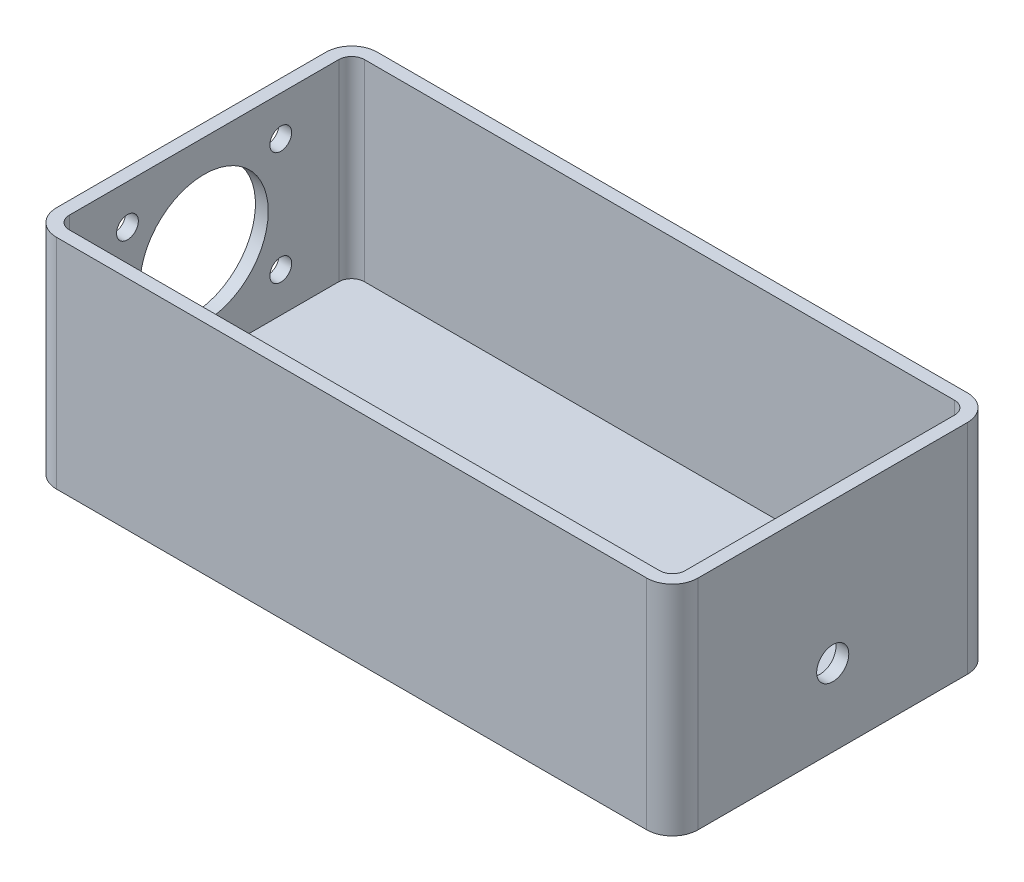
SolidWorks part; units mm, degrees
ref_plane "Front Plane" through (0, 0, 0) normal (0, 0, 1) x (1, 0, 0)
ref_plane "Top Plane" through (0, 0, 0) normal (0, 1, 0) x (1, 0, 0)
ref_plane "Right Plane" through (0, 0, 0) normal (1, 0, 0) x (0, 0, -1)
sketch "Sketch1" plane through (0, 0, 0) normal (0, 1, 0) x (1, 0, 0)
  line L1 (0, 0) -> (127, 0)
  line L2 (0, 0) -> (0, 63.5)
  line L3 (0, 63.5) -> (127, 63.5)
  line L4 (127, 0) -> (127, 63.5)
  dimension "D1" = 63.5
  dimension "D2" = 127
extrude "Boss-Extrude1" add sketch "Sketch1" along normal blind 5.08
sketch "Sketch2" plane through (0, 5.08, 0) normal (0, 1, 0) x (1, 0, 0)
  line L1 (0, 63.5) -> (127, 63.5)
  line L2 (0, 63.5) -> (0, 0)
  line L3 (0, 0) -> (127, 0)
  line L4 (127, 63.5) -> (127, 0)
  line L5 (2.54, 60.96) -> (124.46, 60.96)
  line L6 (2.54, 60.96) -> (2.54, 2.54)
  line L7 (2.54, 2.54) -> (124.46, 2.54)
  line L8 (124.46, 60.96) -> (124.46, 2.54)
  dimension "D1" = 2.54
  dimension "D2" = 2.54
  dimension "D3" = 2.54
  dimension "D4" = 2.54
extrude "Boss-Extrude3" add sketch "Sketch2" along normal blind 38.1
sketch "Sketch3" plane through (0, 0, 0) normal (-1, 0, 0) x (0, 0, 1)
  circle A0 centre (-31.75, 24.13) radius 12.7
  circle A1 centre (-46.9265, 35.3568) radius 2.159
  circle A2 centre (-16.5735, 35.3568) radius 2.159
  circle A3 centre (-46.9265, 12.9032) radius 2.159
  circle A4 centre (-16.5735, 12.9032) radius 2.159
  point P10 (0, 0)
  dimension "D1" = 25.4
  dimension "D2" = 4.318
  dimension "D3" = 4.318
  dimension "D4" = 4.318
  dimension "D5" = 4.318
  dimension "D6" = 30.353
  dimension "D7" = 22.4536
  dimension "D8" = 15.1765
  dimension "D9" = 11.2268
  dimension "D10" = 24.13
  dimension "D11" = 31.75
extrude "Cut-Extrude1" cut sketch "Sketch3" against normal up to next
sketch "Sketch4" plane through (127, 0, 0) normal (1, 0, 0) x (0, 0, -1)
  circle A0 centre (31.75, 15.24) radius 3.175
  dimension "D1" = 15.24
  dimension "D2" = 6.35
  dimension "D3" = 31.75
extrude "Cut-Extrude3" cut sketch "Sketch4" against normal up to next
fillet "Fillet3" radius 5.08 4 edges at (0, 21.59, -63.5) (127, 21.59, -63.5) (127, 21.59, 0) (0, 21.59, 0)
fillet "Fillet4" radius 2.54 4 edges at (2.54, 24.13, -60.96) (2.54, 24.13, -2.54) (124.46, 24.13, -60.96) (124.46, 24.13, -2.54)
